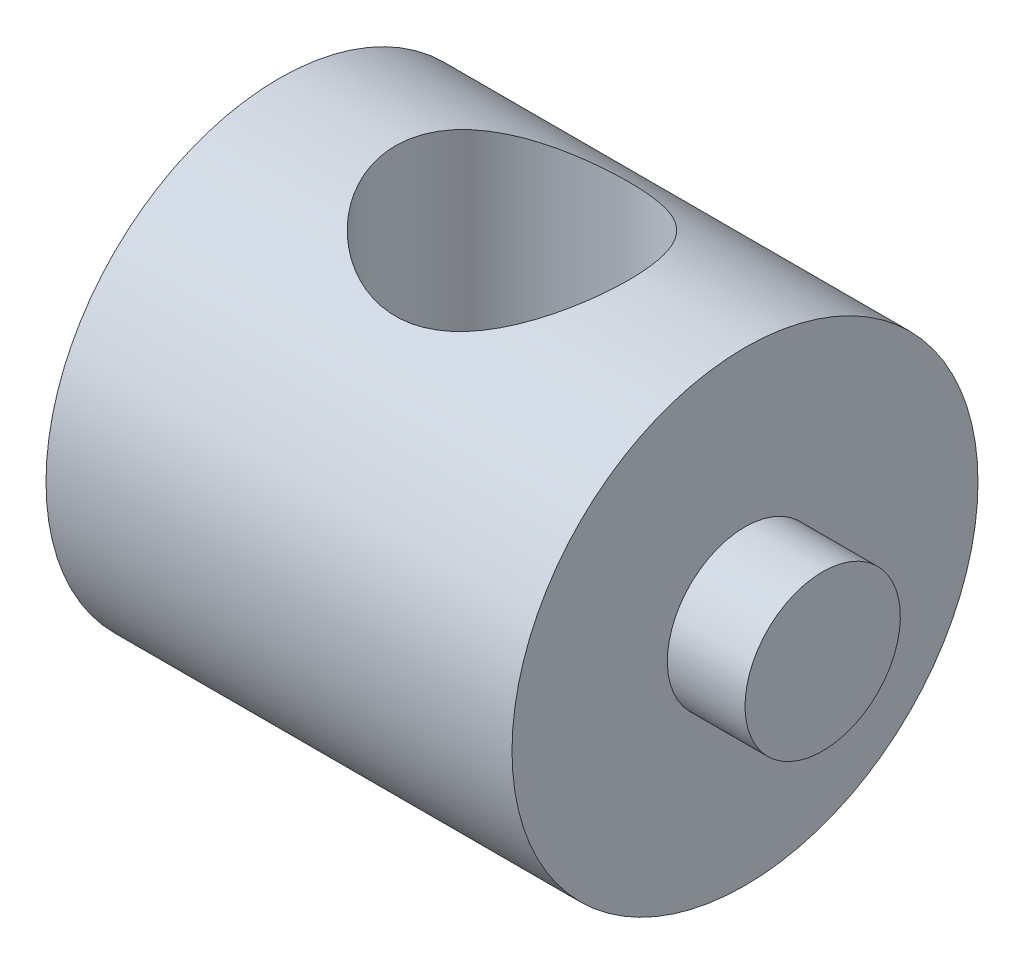
SolidWorks part; units mm, degrees
ref_plane "Front Plane" through (0, 0, 0) normal (0, 0, 1) x (1, 0, 0)
ref_plane "Top Plane" through (0, 0, 0) normal (0, 1, 0) x (1, 0, 0)
ref_plane "Right Plane" through (0, 0, 0) normal (1, 0, 0) x (0, 0, -1)
sketch "Sketch1" plane through (0, 0, 0) normal (0, 0, 1) x (1, 0, 0)
  line L0 (0, 0) -> (0, 9.525)
  line L1 (-9.525, 0) -> (9.525, 0)
  line L2 (-9.525, 9.525) -> (9.525, 9.525)
  line L3 (9.525, 0) -> (9.525, 9.525)
  line L4 (9.525, 0) -> (9.525, 3.175)
  line L5 (9.525, 0) -> (12.7, 0)
  line L6 (9.525, 3.175) -> (12.7, 3.175)
  line L7 (12.7, 0) -> (12.7, 3.175)
  line L8 (0, 0) -> (0, 50000) construction
  line L9 (-12.7, 0) -> (-12.7, 3.175)
  line L10 (-9.525, 3.175) -> (-12.7, 3.175)
  line L11 (-9.525, 0) -> (-9.525, 9.525)
  line L12 (-12.7, 0) -> (-9.525, 0)
  line L13 (12.7, 0) -> (9.525, 0)
  dimension "D1" = 9.525
  dimension "D2" = 3.175
  dimension "D3" = 9.525
  dimension "D4" = 3.175
revolve "Revolve1" add sketch "Sketch1" angle 360 about L13
sketch "Sketch2" plane through (0, 0, 0) normal (0, 1, 0) x (1, 0, 0)
  circle A0 centre (0, 0) radius 4.7625
  dimension "D1" = 9.525
extrude "Cut-Extrude1" cut sketch "Sketch2" against normal through all both and the other way through all
